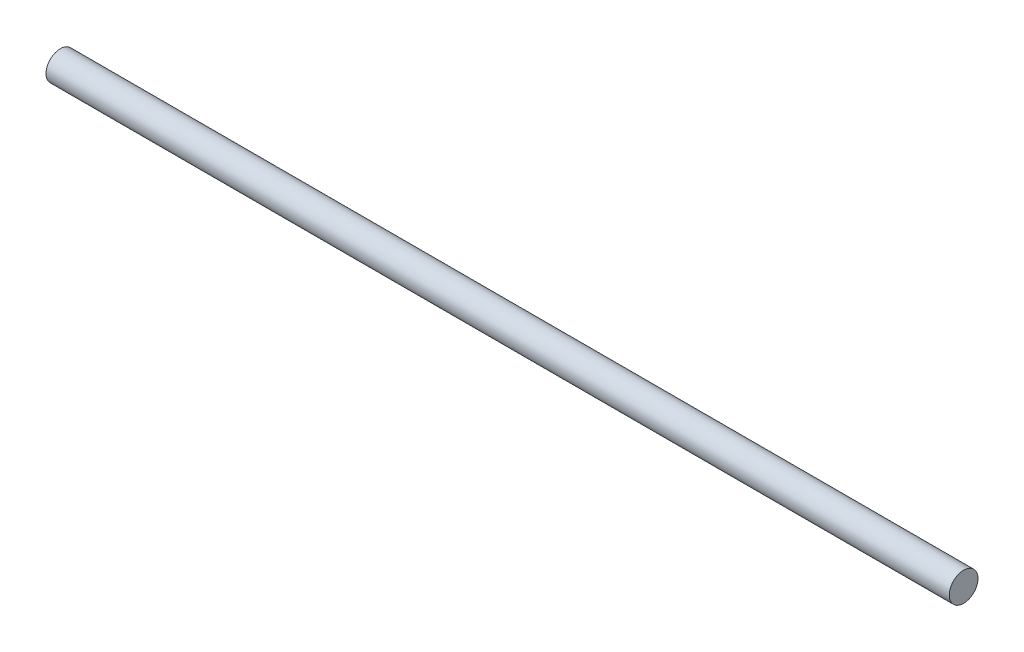
SolidWorks part; units mm, degrees
ref_plane "Front Plane" through (0, 0, 0) normal (0, 0, 1) x (1, 0, 0)
ref_plane "Top Plane" through (0, 0, 0) normal (0, 1, 0) x (1, 0, 0)
ref_plane "Right Plane" through (0, 0, 0) normal (1, 0, 0) x (0, 0, -1)
sketch "Sketch1" plane through (0, 0, 0) normal (0, 1, 0) x (1, 0, 0)
  line L0 (-310.4462, -45.5834) -> (133.7659, -13.1211) construction
  line L1 (133.7659, -13.1211) -> (-41.7007, -13.1211)
  line L2 (-41.7007, -13.1211) -> (-41.7007, -16.1211)
  line L3 (133.7659, -13.1211) -> (133.7659, -16.1211)
  line L4 (-41.7007, -16.1211) -> (133.7659, -16.1211)
  dimension "D1" = 4.18
  dimension "D2" = 175.4666
  dimension "D3" = 3
  dimension "D4" = 3
  dimension "D5" = 90
  dimension "D6" = 90
revolve "Revolve2" add sketch "Sketch1" angle 360 about L1
sketch "Sketch3" plane through (-41.7007, 0, 0) normal (-1, 0, 0) x (0, 0, 1)
  line L0 (10.2163, -0.7498) -> (13.1211, 0) construction
  circle A0 centre (13.1211, 0) radius 3 construction
  circle A1 centre (13.1211, 0) radius 3
extrude "Boss-Extrude1" add sketch "Sketch3" along normal blind 10 contours A1
sketch "Sketch7" plane through (-51.7007, 0, 0) normal (-1, 0, 0) x (0, 0, 1)
  line L0 (13.1211, 0) -> (16.1211, 0) construction
  circle A0 centre (13.1211, 0) radius 3 construction
  circle A1 centre (13.1211, 0) radius 3
extrude "Boss-Extrude5" add sketch "Sketch7" along normal blind 3
